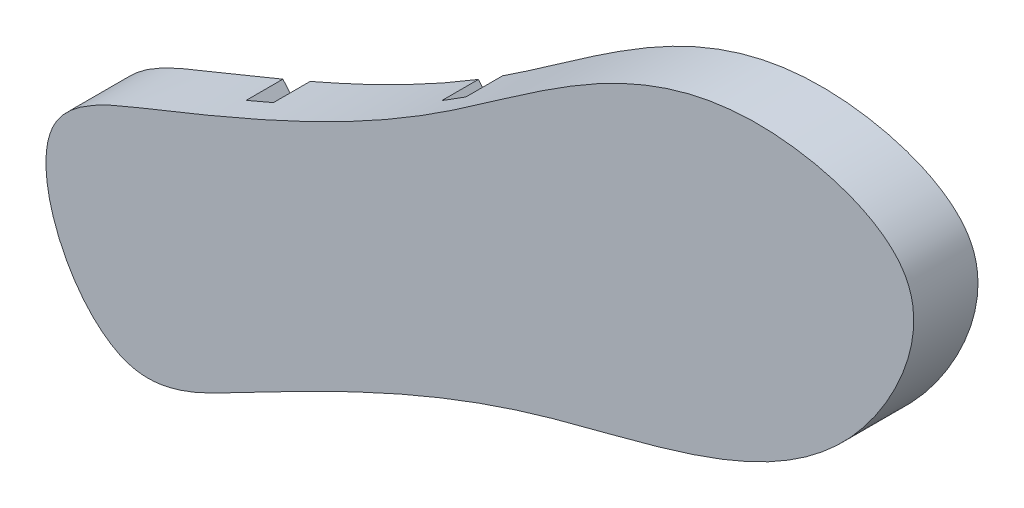
SolidWorks part; units mm, degrees
material "Caucho"
ref_plane "Alzado" through (0, 0, 0) normal (0, 0, 1) x (1, 0, 0)
ref_plane "Planta" through (0, 0, 0) normal (0, 1, 0) x (1, 0, 0)
ref_plane "Vista lateral" through (0, 0, 0) normal (1, 0, 0) x (0, 0, -1)
ref_plane "Plano_goma" through (0, 0, 12.5) normal (0, 0, 1) x (1, 0, 0)
sketch "Sk_Goma" plane through (0, 0, 0) normal (0, 0, 1) x (1, 0, 0)
  spline S0 degree 3 poles (434.3863, 332.3422) (428.9443, 344.1331) (441.1466, 348.8882) (453.6205, 354.2888) (465.9627, 365.6031) (480.5578, 360.8034) (474.7412, 346.583) (458.1239, 344.5314) (445.9213, 338.5429) (434.3863, 332.3422) (428.9443, 344.1331) (441.1466, 348.8882) knots -0.299528 -0.141321 -0.087871 0 0.05345 0.211657 0.387435 0.456064 0.524694 0.700472 0.858679 0.912129 1 1.05345 1.211657 1.387435 only from (431.735, 343.7767) to (431.735, 343.7767)
extrude "Goma" add sketch "Sk_Goma" along normal blind 3.5 from offset 12.5
sketch "Sk_Ranuras_agua" plane through (0, 0, 12.5) normal (0, 0, 1) x (1, 0, 0)
  line L0 (439.9765, 349.7832) -> (441.4292, 350.4537)
  line L1 (441.4292, 350.4537) -> (450.9278, 339.4185)
  line L2 (450.9278, 339.4185) -> (449.4751, 338.748)
  line L3 (449.4751, 338.748) -> (439.9765, 349.7832)
  line L4 (450.872, 354.8119) -> (452.3247, 355.4824)
  line L5 (452.3247, 355.4824) -> (461.8234, 344.4472)
  line L6 (461.8234, 344.4472) -> (460.3706, 343.7767)
  line L7 (460.3706, 343.7767) -> (450.872, 354.8119)
  line L8 (461.7675, 359.8406) -> (463.2202, 360.5111)
  line L9 (463.2202, 360.5111) -> (472.7189, 349.4759)
  line L10 (472.7189, 349.4759) -> (471.2661, 348.8054)
  line L11 (471.2661, 348.8054) -> (461.7675, 359.8406)
extrude "Ranuras_agua" cut sketch "Sk_Ranuras_agua" along normal blind 2
